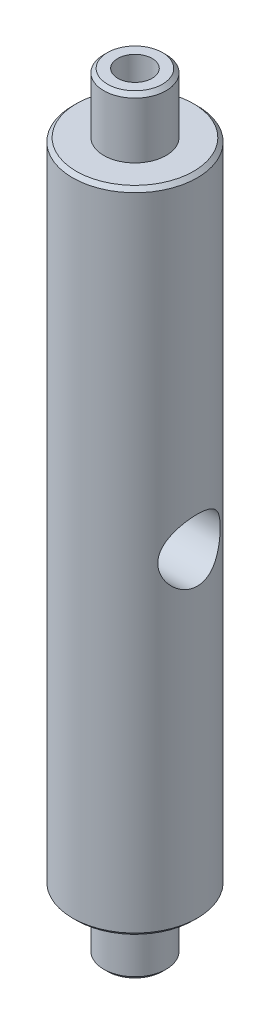
SolidWorks part; units mm, degrees
material "Brass"
ref_plane "Front Plane" through (0, 0, 0) normal (0, 0, 1) x (1, 0, 0)
ref_plane "Top Plane" through (0, 0, 0) normal (0, 1, 0) x (1, 0, 0)
ref_plane "Right Plane" through (0, 0, 0) normal (1, 0, 0) x (0, 0, -1)
sketch "Sketch1" plane through (0, 0, 0) normal (0, 1, 0) x (1, 0, 0)
  circle A0 centre (0, 0) radius 6.35
  dimension "D1" = 12.7
extrude "Main Body Boss-Extrude1" add sketch "Sketch1" along normal blind 66.04
sketch "Sketch2" plane through (0, 0, 0) normal (0, -1, 0) x (1, 0, 0)
  circle A0 centre (0, 0) radius 3.175
  dimension "D1" = 6.35
extrude "Tendon 1 Boss-Extrude2" add sketch "Sketch2" along normal blind 6.096
sketch "Sketch3" plane through (0, 66.04, 0) normal (0, 1, 0) x (1, 0, 0)
  circle A0 centre (0, 0) radius 3.175 construction
  circle A1 centre (0, 0) radius 3.175
extrude "Tendon 2 Boss-Extrude3" add sketch "Sketch3" along normal blind 6.096
sketch "Sketch4" plane through (0, 72.136, 0) normal (0, 1, 0) x (1, 0, 0)
  circle A0 centre (0, 0) radius 1.7526
  dimension "D1" = 3.5052
extrude "10_32 Cut-Extrude1" cut sketch "Sketch4" against normal blind 11.176
sketch "Sketch5" plane through (0, -6.096, 0) normal (0, -1, 0) x (1, 0, 0)
  circle A0 centre (0, 0) radius 1.7526 construction
  circle A1 centre (0, 0) radius 1.7526
extrude "10_32 Cut-Extrude2" cut sketch "Sketch5" against normal blind 11.176
chamfer "Chamfer1" distance 0.381 angle 45 4 edges at (0, 72.136, 3.175) (0, 66.04, 6.35) (0, 0, 6.35) (0, -6.096, -3.175)
sketch "Sketch6" plane through (0, 0, 0) normal (1, 0, 0) x (0, 0, -1)
  line L0 (0, 65.659) -> (0, 0) construction
  line L1 (-6.35, 65.659) -> (6.35, 65.659) construction
  circle A0 centre (0, 32.8295) radius 3.175
  dimension "D1" = 6.35
extrude "Cut-Extrude3" cut sketch "Sketch6" against normal through all and the other way through all
